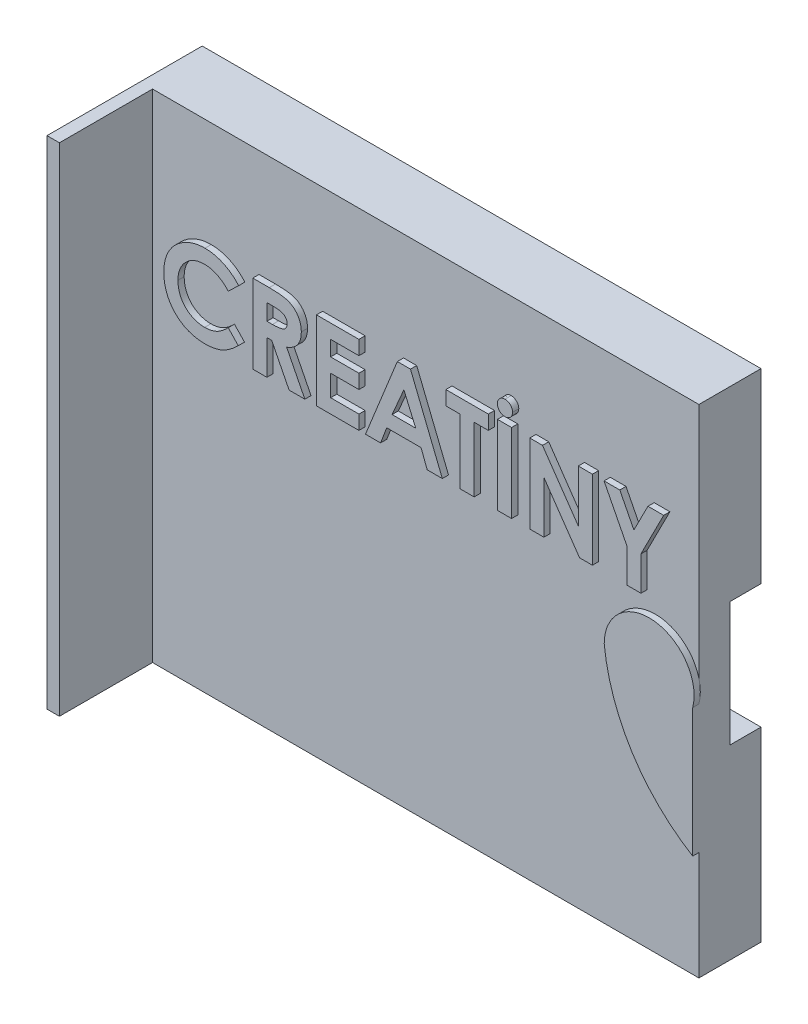
SolidWorks part; units mm, degrees
ref_plane "Ön Düzlem" through (0, 0, 0) normal (0, 0, 1) x (1, 0, 0)
ref_plane "Üst Düzlem" through (0, 0, 0) normal (0, 1, 0) x (1, 0, 0)
ref_plane "Sağ Düzlem" through (0, 0, 0) normal (1, 0, 0) x (0, 0, -1)
sketch "Çizim1" plane through (0, 0, 0) normal (0, 0, 1) x (1, 0, 0)
  line L1 (-45, 40) -> (45, 40)
  line L2 (-45, 40) -> (-45, -40)
  line L3 (-45, -40) -> (45, -40)
  line L4 (45, 40) -> (45, -40)
  line L5 (-45, 40) -> (45, -40) construction
  line L6 (-45, -40) -> (45, 40) construction
  point P0 (0, 0)
  dimension "D1" = 80
  dimension "D2" = 90
extrude "Yükseklik-Ekstrüzyon1" add sketch "Çizim1" along normal mid plane 10
ref_plane "Düzlem1" through (45, 0, 0) normal (1, 0, 0) x (0, 0, -1)
sketch "Çizim2" plane through (45, 0, 0) normal (1, 0, 0) x (0, 0, -1)
  line L0 (5, -40) -> (5, 40) construction
  line L1 (0, 10) -> (5, 10)
  line L2 (0, 10) -> (0, -10)
  line L3 (0, -10) -> (5, -10)
  line L4 (5, 10) -> (5, -10)
  line L5 (0, 10) -> (5, -10) construction
  line L6 (0, -10) -> (5, 10) construction
  point P0 (2.5, 0)
  dimension "D1" = 5
  dimension "D2" = 20
extrude "Kes-Ekstrüzyon1" cut sketch "Çizim2" against normal blind 50
ref_plane "Düzlem2" through (-45, 0, 0) normal (1, 0, 0) x (0, 0, -1)
sketch "Çizim3" plane through (-45, 0, 0) normal (1, 0, 0) x (0, 0, -1)
  line L0 (-5, 40) -> (-5, -40) construction
  line L2 (-20, 40) -> (-5, 40)
  line L3 (-20, 40) -> (-20, -40)
  line L4 (-20, -40) -> (-5, -40)
  line L5 (-5, 40) -> (-5, -40)
  line L6 (-20, 40) -> (-5, -40) construction
  line L7 (-20, -40) -> (-5, 40) construction
  point P1 (-12.5, 0)
  dimension "D1" = 15
  dimension "D2" = 80
extrude "Yükseklik-Ekstrüzyon2" add sketch "Çizim3" along normal blind 2
sketch "Çizim4" plane through (0, 0, 5) normal (0, 0, 1) x (1, 0, 0)
  line L0 (45, -5.5) -> (45, 5.5) construction
  line L1 (45, 40) -> (-43, 40) construction
  line L2 (-43, -40) -> (-43, 40) construction
  line L3 (45, -1.7892) -> (45, -22.5)
  line L4 (-43, -40) -> (45, -40) construction
  arc A0 (45, -1.7892) -> (30.7446, 0) centre (37.9846, 0) ccw
  arc A1 (30.7446, 0) -> (45, -22.5) centre (60.5801, 3.1371) ccw
  text T0 "CREATİNY" font "Century Gothic" height in points 48
  dimension "D4" = 7.24
  dimension "D5" = 30
  dimension "D1" = 30
  dimension "D2" = 2
  dimension "D3" = 40
  dimension "D6" = 17.5
extrude "Yükseklik-Ekstrüzyon3" add sketch "Çizim4" along normal blind 1
